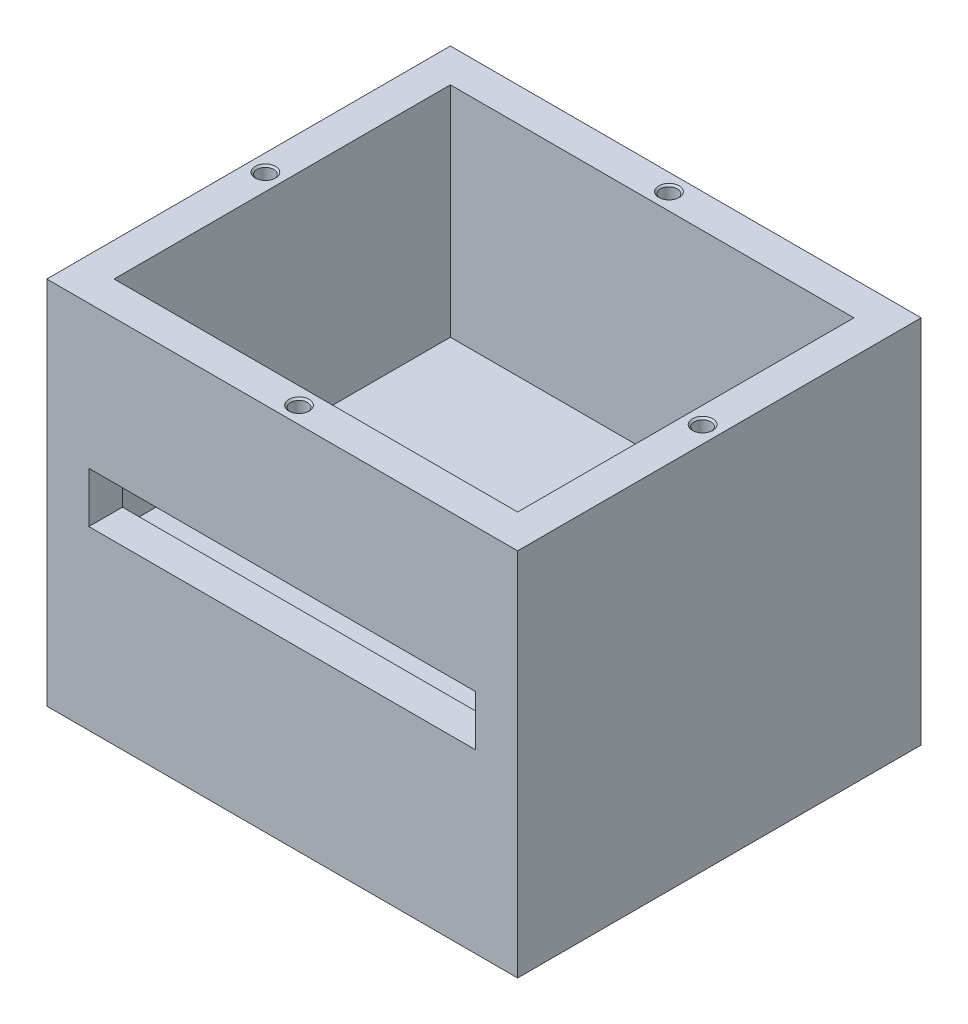
SolidWorks part; units mm, degrees
ref_plane "前视基准面" through (0, 0, 0) normal (0, 0, 1) x (1, 0, 0)
ref_plane "上视基准面" through (0, 0, 0) normal (0, 1, 0) x (1, 0, 0)
ref_plane "右视基准面" through (0, 0, 0) normal (1, 0, 0) x (0, 0, -1)
other "Configuration Table"
sketch "Box_top_view" plane through (0, 0, 0) normal (0, 1, 0) x (1, 0, 0)
  line L1 (-70, -60) -> (70, -60)
  line L2 (-70, -60) -> (-70, 60)
  line L3 (-70, 60) -> (70, 60)
  line L4 (70, -60) -> (70, 60)
  point P4 (-70, 0)
  point P6 (0, 60)
  dimension "D1" = 140
  dimension "D2" = 120
extrude "Box_extrude_part" add sketch "Box_top_view" along normal blind 110
sketch "Scissor_crossSection" plane through (0, 0, 60) normal (0, 0, 1) x (1, 0, 0)
  line L0 (-70, 0) -> (70, 0) construction
  line L1 (-57.5, 67.5) -> (57.5, 67.5)
  line L2 (-57.5, 67.5) -> (-57.5, 52.5)
  line L3 (-57.5, 52.5) -> (57.5, 52.5)
  line L4 (57.5, 67.5) -> (57.5, 52.5)
  point P4 (0, 67.5)
  point P6 (57.5, 60)
  dimension "D1" = 15
  dimension "D2" = 115
  dimension "D3" = 60
sketch "Inner_box_cut" plane through (0, 110, 0) normal (0, 1, 0) x (1, 0, 0)
  line L1 (-60, 50) -> (60, 50)
  line L2 (-60, 50) -> (-60, -50)
  line L3 (-60, -50) -> (60, -50)
  line L4 (60, 50) -> (60, -50)
  point P5 (0, 50)
  point P7 (-60, 0)
  dimension "D1" = 120
  dimension "D2" = 100
extrude "Inner_box_cut_1" cut sketch "Inner_box_cut" against normal blind 65
extrude "Scissor_corssSection_cut" cut sketch "Scissor_crossSection" against normal blind 10
sketch "Shaft_location" plane through (0, 45, 0) normal (0, 1, 0) x (1, 0, 0)
  line L0 (0, 21.009) -> (0, -18.7201) construction
  circle A0 centre (15, 0) radius 7.5
  circle A1 centre (-15, 0) radius 7.5
  dimension "D1" = 15
  dimension "D2" = 15
extrude "Shaft_location_cut" cut sketch "Shaft_location" against normal blind 35 contours A0 | A1
sketch "Sketch2" plane through (0, 45, 0) normal (0, 1, 0) x (1, 0, 0)
  line L0 (0, 22.1535) -> (0, -20.3551) construction
  circle A1 centre (-15, 0) radius 14
  circle A2 centre (15, 0) radius 14
  dimension "D1" = 28
extrude "Cut-Extrude2" cut sketch "Sketch2" against normal blind 10
sketch "Hole_location" plane through (0, 110, 0) normal (0, 1, 0) x (1, 0, 0)
  line L0 (0, 30.1647) -> (0, -21.1725) construction
  line L1 (-34.0069, 0) -> (33.6799, 0) construction
  point P5 (-65, 0)
  point P6 (0, 55)
  dimension "D1" = 65
  dimension "D2" = 55
hole_wizard "M6 Tapped Hole3" positions "3DSketch3" profile "Sketch7" tap size "M6" standard "ISO"
sketch3d "3DSketch3"
  point P0 (0, 110, -55)
  point P3 (-65, 110, 0)
cosmetic thread "Hole Thread7" parameters "D1"=10, "D2"=6
cosmetic thread "Hole Thread8" parameters "D1"=10, "D2"=6
sketch "Sketch7" plane through (0, 110, -55) normal (1, 0, 0) x (0, 0, 1)
  line L0 (0, 0) -> (0, 14.5022)
  line L1 (0, 14.5022) -> (2.5, 13)
  line L2 (2.5, 13) -> (2.5, 0.525)
  line L3 (2.5, 0.525) -> (3.025, 0)
  line L5 (3.025, 0) -> (0, 0)
  line L6 (-2.5, 0.525) -> (-3.025, 0) construction
  line L10 (0, 14.5022) -> (-2.5, 13) construction
  line L11 (0, -6.35) -> (0, 107.95) construction
  dimension "Tap Drill Dia." = 5
  dimension "Tap Drill Depth" = 13
  dimension "Near C'Sink Dia." = 6.05
  dimension "Near C'Sink Angle" = 90
  dimension "Drill Angle" = 118
mirror "M6_hole_mirror" about plane through (0, 0, 0) normal (1, 0, 0) of "M6 Tapped Hole3" second plane through (0, 0, 0) second plane normal (0, 0, 1)
